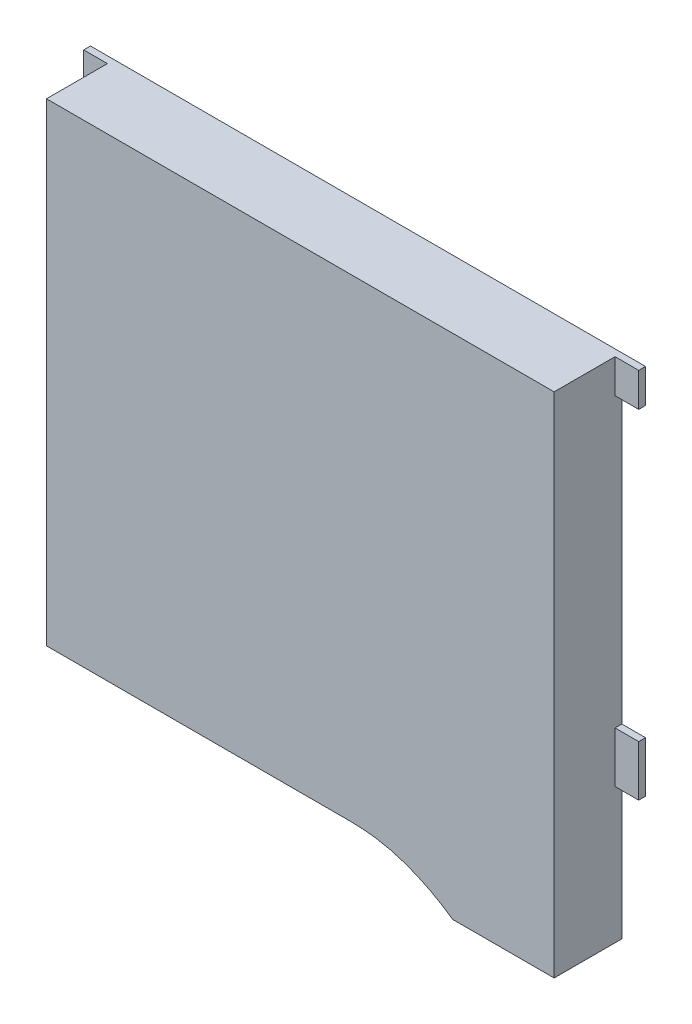
SolidWorks part; units mm, degrees
ref_plane "Front Plane" through (0, 0, 0) normal (0, 0, 1) x (1, 0, 0)
ref_plane "Top Plane" through (0, 0, 0) normal (0, 1, 0) x (1, 0, 0)
ref_plane "Right Plane" through (0, 0, 0) normal (1, 0, 0) x (0, 0, -1)
sketch "Sketch1" plane through (0, 0, 0) normal (0, 0, 1) x (1, 0, 0)
  line L0 (-7.5, 7.5) -> (7.5, 7.5)
  line L1 (7.5, 7.5) -> (7.5, -7.5)
  line L2 (7.5, -7.5) -> (4.5, -7.5)
  line L3 (-7.5, 7.5) -> (-7.5, -6.5)
  line L4 (-7.5, -6.5) -> (1.5, -6.5)
  line L5 (0, 0) -> (0, 7.5) construction
  line L6 (0, 0) -> (7.5, 0) construction
  spline S0 degree 2 poles (1.5, -6.5) (3.0811, -6.5) (4.5, -7.5) knots 0 0 0 1 1 1
  dimension "D1" = 15
  dimension "D2" = 15
  dimension "D3" = 3
  dimension "D4" = 9
  dimension "D5" = 14
extrude "Boss-Extrude1" add sketch "Sketch1" along normal blind 2
sketch "Sketch2" plane through (0, -7.5, 0) normal (0, -1, 0) x (1, 0, 0)
  line L0 (-7.5, 2) -> (1.5, 2) construction
  line L1 (-6.5, 1.8) -> (4.5, 1.8)
  line L2 (-6.5, 1.8) -> (-6.5, 0.7)
  line L3 (-6.5, 0.7) -> (4.5, 0.7)
  line L4 (4.5, 1.8) -> (4.5, 0.7)
  line L5 (-7.5, 2) -> (-7.5, 0) construction
  line L6 (-7.5, 0) -> (1.5, 0) construction
  line L7 (7.5, 2) -> (7.5, 0) construction
  dimension "D1" = 0.2
  dimension "D2" = 1
  dimension "D3" = 0.7
  dimension "D4" = 3
extrude "Cut-Extrude1" cut sketch "Sketch2" against normal blind 12
sketch "Sketch3" plane through (0, 0, 0) normal (0, 0, 1) x (1, 0, 0)
  line L0 (7.5, 7.5) -> (8.2, 7.5)
  line L1 (8.2, 7.5) -> (8.2, 6.5)
  line L2 (8.2, 6.5) -> (7.5, 6.5)
  line L3 (7.5, -7.5) -> (7.5, 7.5) construction
  line L4 (7.5, 6.5) -> (7.5, 7.5)
  line L5 (-7.5, 7.5) -> (-7.5, -6.5) construction
  line L6 (-7.5, 7.5) -> (-8.2, 7.5)
  line L7 (-7.5, 7.5) -> (-7.5, 6.5)
  line L8 (-7.5, 6.5) -> (-8.2, 6.5)
  line L9 (-8.2, 7.5) -> (-8.2, 6.5)
  line L10 (-7.5, -2) -> (-8.2, -2)
  line L11 (-7.5, -2) -> (-7.5, -3.5)
  line L12 (-7.5, -3.5) -> (-8.2, -3.5)
  line L13 (-8.2, -2) -> (-8.2, -3.5)
  line L15 (7.5, -2) -> (8.2, -2)
  line L16 (7.5, -2) -> (7.5, -3.5)
  line L17 (7.5, -3.5) -> (8.2, -3.5)
  line L18 (8.2, -2) -> (8.2, -3.5)
  dimension "D1" = 1
  dimension "D2" = 1.5
  dimension "D3" = 0.7
  dimension "D4" = 9.5
extrude "Boss-Extrude2" add sketch "Sketch3" along normal blind 0.2
